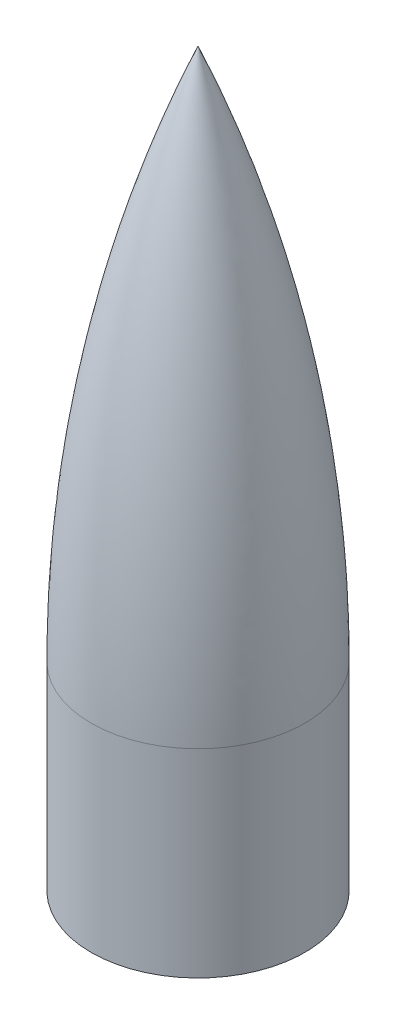
SolidWorks part; units mm, degrees
other "Markup1"
sketch "Sketch4" plane through (78.16, -154.2442, 78.16) normal (0.9651, -0.1718, 0.1975) x (-0.1686, -0.9851, -0.0334)
material "A-Glass Fiber"
ref_plane "Front Plane" through (0, 0, 0) normal (0, 0, 1) x (1, 0, 0)
ref_plane "Top Plane" through (0, 0, 0) normal (0, 1, 0) x (1, 0, 0)
ref_plane "Right Plane" through (0, 0, 0) normal (1, 0, 0) x (0, 0, -1)
sketch "Sketch1" plane through (0, 0, 0) normal (0, 0, 1) x (1, 0, 0)
  line L3 (0, 0) -> (0, 398.8705) construction
  line L6 (0, 400) -> (0, 402.7567)
  line L9 (0, 400) -> (0, 396.4892)
  line L10 (78.35, 0) -> (-964.0394, 0) construction
  line L11 (0, 411.0234) -> (0, 614.1078) construction
  line L14 (78.35, 0) -> (78.35, -150)
  line L15 (78.35, -150) -> (80.75, -150)
  line L16 (80.75, 0) -> (80.75, -150)
  arc A0 (78.35, 0) -> (0, 396.4892) centre (-964.0394, 0) ccw
  arc A1 (80.75, 0) -> (0, 402.7567) centre (-964.0394, 0) ccw
  circle A2 centre (-964.0394, 0) radius 1042.3894 construction
  circle A3 centre (-964.0394, 0) radius 1044.7894 construction
  point P11 (0, 400)
  dimension "D5" = 1042.3894
  dimension "D1" = 400
  dimension "D2" = 3.5108
  dimension "D3" = 2.4
  dimension "D4" = 78.35
  dimension "D6" = 150
  dimension "D7" = 2.4
revolve "Revolve3" add sketch "Sketch1" angle 360 about L6
